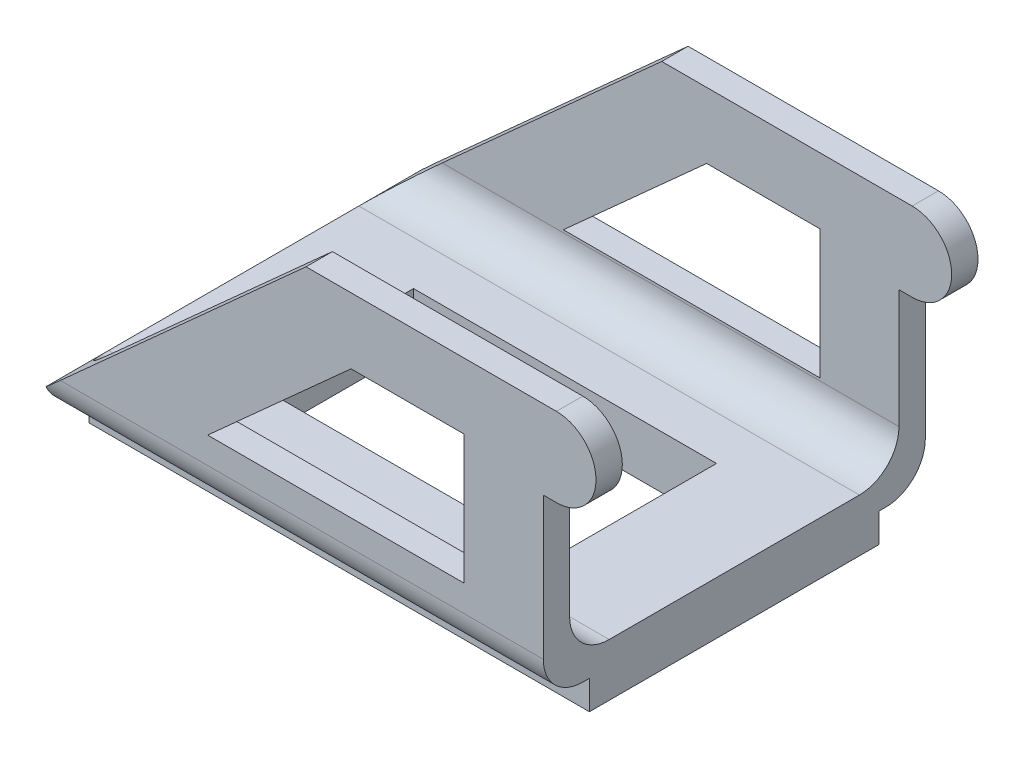
SolidWorks part; units mm, degrees
ref_plane "Front Plane" through (0, 0, 0) normal (0, 0, 1) x (1, 0, 0)
ref_plane "Top Plane" through (0, 0, 0) normal (0, 1, 0) x (1, 0, 0)
ref_plane "Right Plane" through (0, 0, 0) normal (1, 0, 0) x (0, 0, -1)
sketch "Sketch1" plane through (0, 0, 0) normal (0, 1, 0) x (1, 0, 0)
  line L1 (-19, -11) -> (19, -11)
  line L2 (-19, -11) -> (-19, 11)
  line L3 (-19, 11) -> (19, 11)
  line L4 (19, -11) -> (19, 11)
  line L5 (-19, -11) -> (19, 11) construction
  line L6 (-19, 11) -> (19, -11) construction
  line L7 (-11.5, -6.15) -> (11.5, -6.15)
  line L8 (-11.5, -6.15) -> (-11.5, 6.15)
  line L9 (-11.5, 6.15) -> (11.5, 6.15)
  line L10 (11.5, -6.15) -> (11.5, 6.15)
  line L11 (-11.5, -6.15) -> (11.5, 6.15) construction
  line L12 (-11.5, 6.15) -> (11.5, -6.15) construction
  point P0 (0, 0)
  point P6 (0, 0)
  dimension "D1" = 38
  dimension "D2" = 22
  dimension "D3" = 23
  dimension "D4" = 12.3
extrude "Boss-Extrude1" add sketch "Sketch1" along normal blind 4
sketch "Sketch2" plane through (-19, 0, 0) normal (-1, 0, 0) x (0, 0, 1)
  line L0 (-11, 0) -> (11, 0) construction
  line L1 (-14.5, 9.7999) -> (14.5, 9.7999) construction
  line L2 (-11, 2.2) -> (-14.5, 2.2)
  line L3 (-11, 4) -> (-11, 0) construction
  line L4 (-14.5, 2.2) -> (-14.5, 22)
  line L5 (-14.5, 22) -> (-12.5, 22)
  line L6 (-12.5, 22) -> (-12.5, 4)
  line L7 (-12.5, 4) -> (-11, 4)
  line L8 (-11, 4) -> (11, 4) construction
  line L9 (-11, 4) -> (-11, 2.2)
  line L10 (0, -12.1) -> (0, 12.1) construction
  line L11 (12.5, 4) -> (11, 4)
  line L12 (12.5, 22) -> (12.5, 4)
  line L13 (14.5, 22) -> (12.5, 22)
  line L14 (14.5, 2.2) -> (14.5, 22)
  line L15 (11, 2.2) -> (14.5, 2.2)
  line L16 (11, 4) -> (11, 2.2)
  point P0 (0, 9.7999)
  dimension "D1" = 29
  dimension "D2" = 2
  dimension "D3" = 1.8
  dimension "D4" = 22
extrude "Boss-Extrude2" add sketch "Sketch2" against normal blind 42
fillet "Fillet1" radius 3 4 edges at (2, 2.2, 14.5) (2, 2.2, -14.5) (2, 4, 12.5) (2, 4, -12.5)
sketch "Sketch4" plane through (0, 0, -14.5) normal (0, 0, -1) x (-1, 0, 0)
  line L0 (19, 4) -> (-0.991, 22)
  line L1 (19, 2.2) -> (19, 5.2) construction
  line L2 (-23, 22) -> (19, 22) construction
  line L3 (-20, 16) -> (-19, 16)
  line L4 (-19, 16) -> (-19, 1.1538)
  line L8 (-23, 22) -> (-23, 5.2) construction
  line L9 (-19, 1.1538) -> (-23, 1.1538)
  line L13 (-0.991, 22) -> (19, 22)
  line L14 (19, 22) -> (19, 4)
  line L16 (-19, 0) -> (19, 0) construction
  line L17 (-19, 2.2) -> (-19, 0) construction
  line L18 (-20, 22) -> (-23, 22)
  line L19 (-23, 22) -> (-23, 1.1538)
  arc A0 (-20, 22) -> (-20, 16) centre (-20, 19) ccw
  dimension "D3" = 3
  dimension "D2" = 4
extrude "Cut-Extrude1" cut sketch "Sketch4" against normal through all
sketch "Sketch6" plane through (0, 0, -14.5) normal (0, 0, -1) x (-1, 0, 0)
  line L0 (6.4792, 7.2) -> (-13, 7.2)
  line L1 (-13, 7.2) -> (-13, 17)
  line L2 (-13, 17) -> (-4.4048, 17)
  line L3 (-4.4048, 17) -> (6.4792, 7.2)
  line L4 (17.6673, 5.2) -> (-0.991, 22) construction
  line L5 (-20, 22) -> (-0.991, 22) construction
  line L6 (-19, 5.2) -> (17.6673, 5.2) construction
  line L7 (-19, 16) -> (-19, 5.2) construction
  dimension "D1" = 5
  dimension "D2" = 2
  dimension "D3" = 6
  dimension "D4" = 6
extrude "Cut-Extrude2" cut sketch "Sketch6" against normal through all
sketch "Sketch7" plane through (0, 0, -14.5) normal (0, 0, -1) x (-1, 0, 0)
  line L0 (-19, 16) -> (-19, 22) construction
  line L1 (-20, 22) -> (-0.991, 22) construction
  circle A0 centre (-20, 19) radius 1
  dimension "D1" = 2
extrude "Boss-Extrude3" add sketch "Sketch7" along normal blind 1.2
fillet "Fillet2" radius 0.5 1 edges at (19, 19, -15.7)
